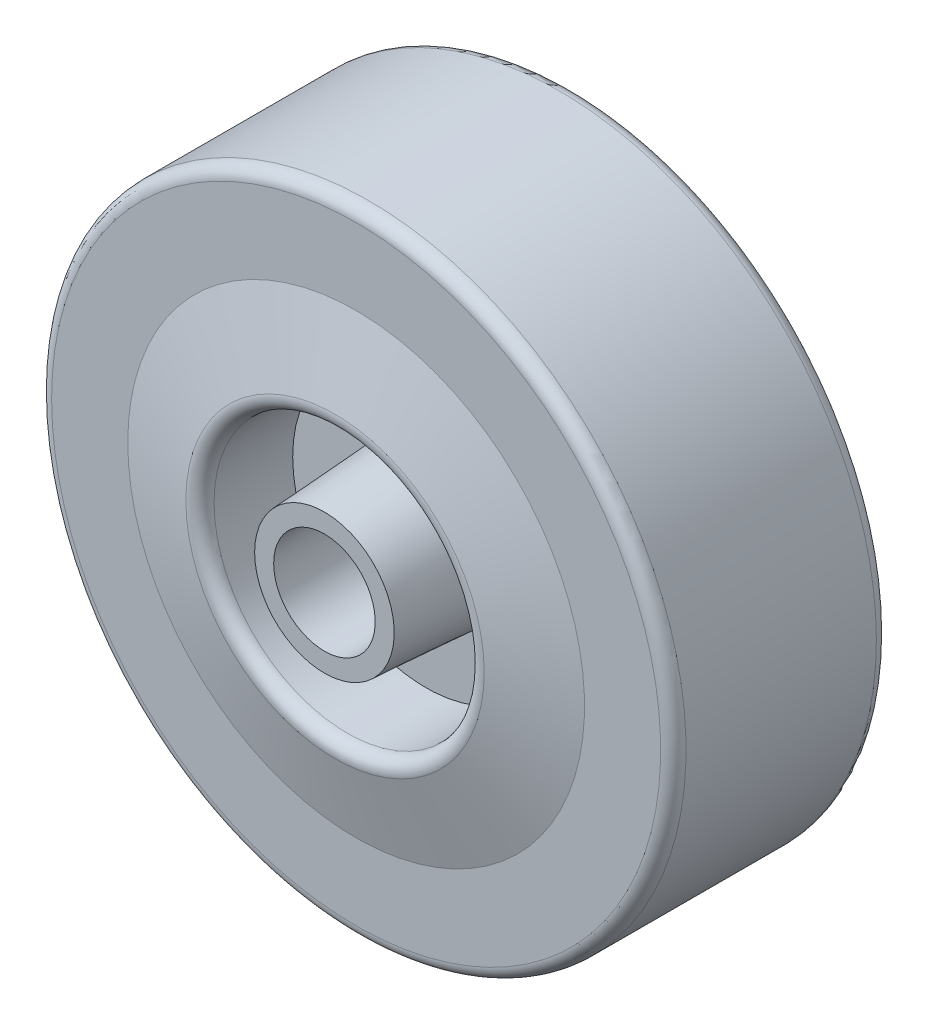
SolidWorks part; units mm, degrees
material "EPDM"
ref_plane "Plan de face" through (0, 0, 0) normal (0, 0, 1) x (1, 0, 0)
ref_plane "Plan de dessus" through (0, 0, 0) normal (0, 1, 0) x (1, 0, 0)
ref_plane "Plan de droite" through (0, 0, 0) normal (1, 0, 0) x (0, 0, -1)
sketch "Esquisse1" plane through (0, 0, 0) normal (0, 1, 0) x (1, 0, 0)
  line L0 (0, 12.6051) -> (0, -10.3469) construction
  line L1 (0, 0) -> (4, 0) construction
  line L2 (4, -11) -> (4, 11)
  line L3 (4, 11) -> (5.5, 11)
  line L4 (5.5, 11) -> (6, 3)
  line L5 (6, 3) -> (10.5, 3)
  line L6 (10.5, 3) -> (10.5, 10.5)
  line L7 (10.5, 10.5) -> (18, 8.5)
  line L8 (18, 8.5) -> (25, 8.5)
  line L9 (25, 8.5) -> (25, -8.5)
  line L10 (25, 0) -> (4, 0) construction
  line L11 (4, -11) -> (5.5, -11)
  line L12 (5.5, -11) -> (6, -3)
  line L13 (6, -3) -> (10.5, -3)
  line L14 (10.5, -3) -> (10.5, -10.5)
  line L15 (10.5, -10.5) -> (18, -8.5)
  line L16 (18, -8.5) -> (25, -8.5)
  point P5 (25, 0)
  dimension "D1" = 4
  dimension "D2" = 25
  dimension "D3" = 1.5
  dimension "D4" = 2
  dimension "D5" = 5
  dimension "D6" = 8.5
  dimension "D7" = 10.5
  dimension "D8" = 7.5
  dimension "D9" = 11
  dimension "D10" = 8
revolve "Révolution1" add sketch "Esquisse1" angle 360 about L0
fillet "Congé1" radius 1 2 edges at (-25, 0, 8.5) (-25, 0, -8.5)
fillet "Congé2" radius 1 2 edges at (-10.5, 0, -10.5) (-10.5, 0, 10.5)
